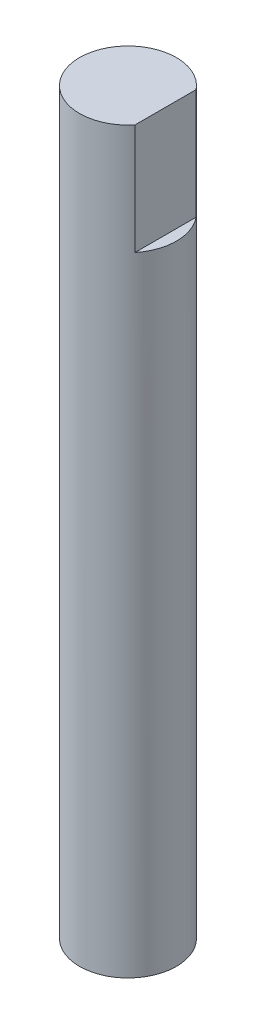
SolidWorks part; units mm, degrees
ref_plane "Front Plane" through (0, 0, 0) normal (0, 0, 1) x (1, 0, 0)
ref_plane "Top Plane" through (0, 0, 0) normal (0, 1, 0) x (1, 0, 0)
ref_plane "Right Plane" through (0, 0, 0) normal (1, 0, 0) x (0, 0, -1)
sketch "Sketch1" plane through (0, 0, 0) normal (0, 1, 0) x (1, 0, 0)
  circle A0 centre (0, 0) radius 2.5
  dimension "D1" = 5
extrude "Boss-Extrude1" add sketch "Sketch1" along normal blind 38.1
sketch "Sketch2" plane through (0, 38.1, 0) normal (0, 1, 0) x (1, 0, 0)
  line L0 (1.94, 1.5768) -> (1.94, -1.5768)
  line L1 (-2.5, 4.6843) -> (-2.5, -2.1) construction
  circle A1 centre (0, 0) radius 2.5
  arc A2 (1.94, -1.5768) -> (1.94, 1.5768) centre (0, 0) ccw
  dimension "D2" = 4.44
  dimension "D1" = 0
extrude "Cut-Extrude1" cut sketch "Sketch2" against normal blind 5.7
